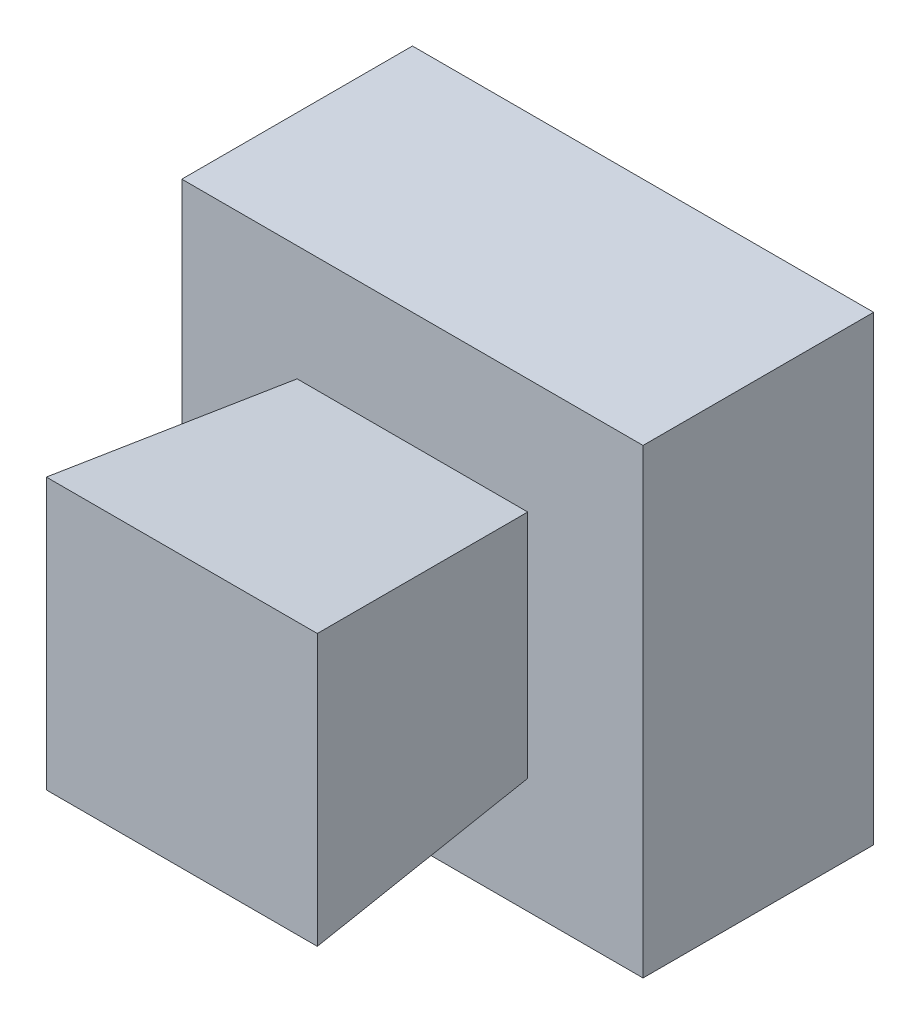
SolidWorks part; units mm, degrees
ref_plane "前视基准面" through (0, 0, 0) normal (0, 0, 1) x (1, 0, 0)
ref_plane "上视基准面" through (0, 0, 0) normal (0, 1, 0) x (1, 0, 0)
ref_plane "右视基准面" through (0, 0, 0) normal (1, 0, 0) x (0, 0, -1)
other "Configuration Table"
sketch "草图1" plane through (0, 0, 0) normal (0, 0, 1) x (1, 0, 0)
  line L1 (0, 0) -> (20, 0)
  line L2 (0, 0) -> (0, 20)
  line L3 (0, 20) -> (20, 20)
  line L4 (20, 0) -> (20, 20)
extrude "BaseBox" add sketch "草图1" along normal blind 10
sketch "草图2" plane through (0, 0, 10) normal (0, 0, 1) x (1, 0, 0)
  line L1 (5, 5) -> (15, 5)
  line L2 (5, 5) -> (5, 15)
  line L3 (5, 15) -> (15, 15)
  line L4 (15, 5) -> (15, 15)
extrude "DraftOutward" add sketch "草图2" along normal blind 10 draft 5 draft outward yes
